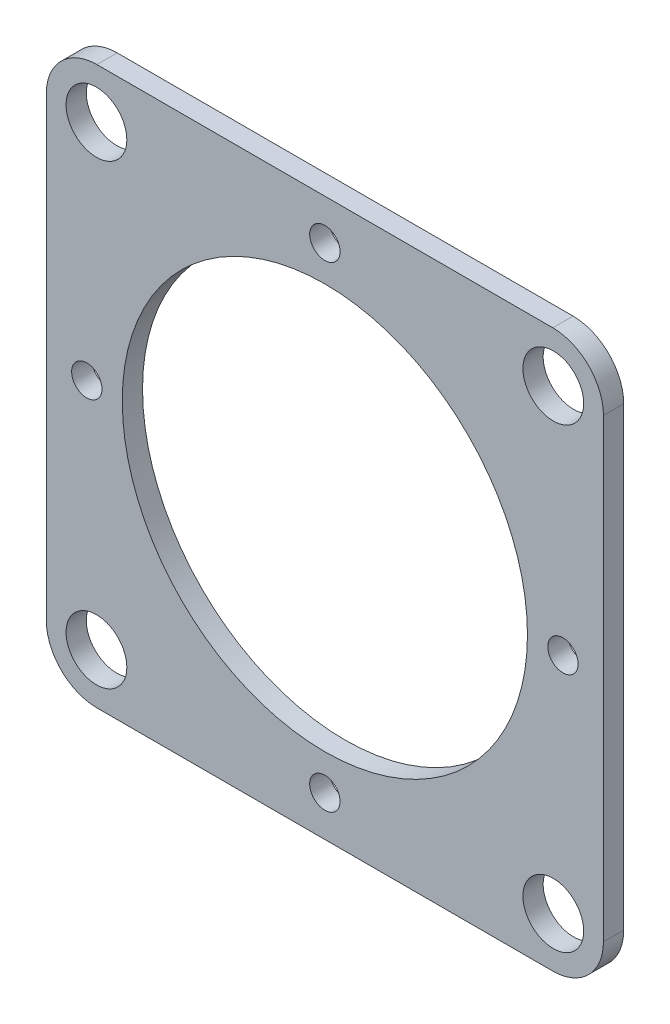
SolidWorks part; units mm, degrees
material "Thornel Mat VMA"
ref_plane "Alzado" through (0, 0, 0) normal (0, 0, 1) x (1, 0, 0)
ref_plane "Planta" through (0, 0, 0) normal (0, 1, 0) x (1, 0, 0)
ref_plane "Vista lateral" through (0, 0, 0) normal (1, 0, 0) x (0, 0, -1)
sketch "Croquis1" plane through (0, 0, 0) normal (0, 0, 1) x (1, 0, 0)
  line L0 (0, 0) -> (0, 27.5) construction
  line L1 (27.5, -27.5) -> (-27.5, -27.5)
  line L2 (27.5, -27.5) -> (27.5, 27.5)
  line L3 (27.5, 27.5) -> (-27.5, 27.5)
  line L4 (-27.5, -27.5) -> (-27.5, 27.5)
  line L5 (27.5, -27.5) -> (-27.5, 27.5) construction
  line L6 (27.5, 27.5) -> (-27.5, -27.5) construction
  circle A0 centre (0, 0) radius 20
  circle A1 centre (-22.5503, 22.5503) radius 3
  circle A2 centre (22.5503, 22.5503) radius 3
  circle A3 centre (22.5503, -22.5503) radius 3
  circle A4 centre (-22.5503, -22.5503) radius 3
  circle A5 centre (0, 23.5) radius 1.5
  circle A6 centre (23.5, 0) radius 1.5
  circle A7 centre (0, -23.5) radius 1.5
  circle A8 centre (-23.5, 0) radius 1.5
  point P0 (0, 0)
  point P19 (0, 0)
  point P28 (0, 0)
  dimension "D1" = 40
  dimension "D3" = 6
  dimension "D7" = 4
  dimension "D9" = 3
  dimension "D2" = 7
  dimension "D4" = 55
  dimension "D5" = 55
  dimension "D6" = 4
  dimension "D8" = 4
extrude "Saliente-Extruir1" add sketch "Croquis1" along normal blind 2
fillet "Redondeo1" radius 5 4 edges at (27.5, -27.5, 1) (-27.5, -27.5, 1) (27.5, 27.5, 1) (-27.5, 27.5, 1)
